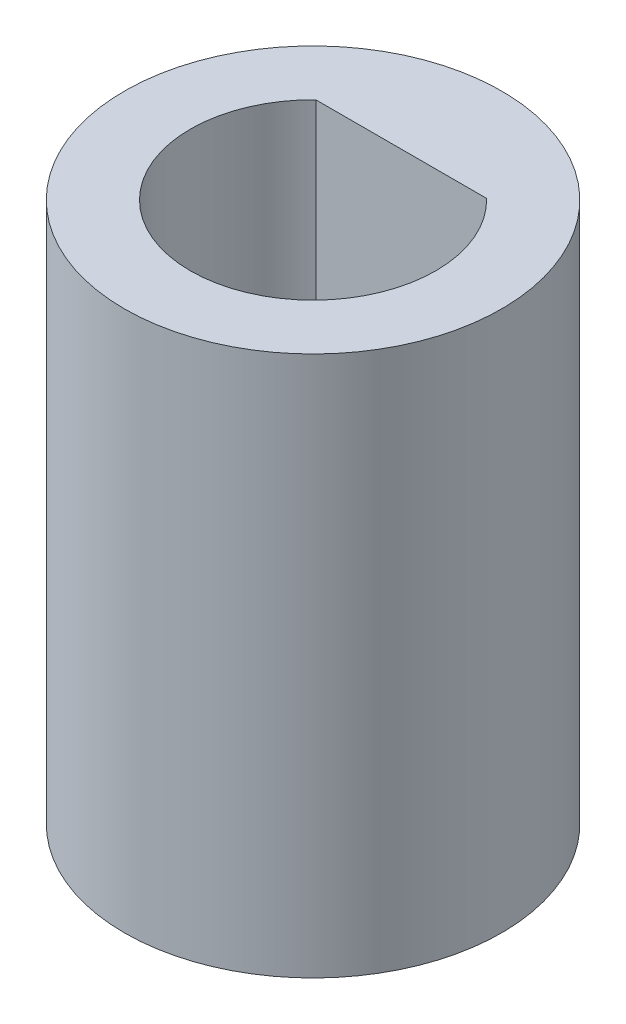
SolidWorks part; units mm, degrees
ref_plane "Front Plane" through (0, 0, 0) normal (0, 0, 1) x (1, 0, 0)
ref_plane "Top Plane" through (0, 0, 0) normal (0, 1, 0) x (1, 0, 0)
ref_plane "Right Plane" through (0, 0, 0) normal (1, 0, 0) x (0, 0, -1)
sketch "Sketch1" plane through (0, 0, 0) normal (0, 1, 0) x (1, 0, 0)
  line L0 (-2.5923, 2.675) -> (2.5923, 2.675) construction
  circle A0 centre (0, 0) radius 5.725
  circle A1 centre (0, 0) radius 3.725 construction
  arc A2 (-2.5923, 2.675) -> (2.5923, 2.675) centre (0, 0) ccw construction
  point P6 (0, -3.725)
  dimension "D1" = 7.45
  dimension "D2" = 2
  dimension "D3" = 6.4
extrude "Boss-Extrude1" add sketch "Sketch1" against normal blind 16.4
ref_plane "Plane1" through (0, 0, 0) normal (0, 1, 0) x (1, 0, 0)
sketch "Sketch3" plane through (0, 0, 0) normal (0, 1, 0) x (1, 0, 0)
  line L0 (-2.5923, 2.675) -> (2.5923, 2.675) construction
  line L1 (-2.5923, 2.675) -> (2.5923, 2.675)
  circle A0 centre (0, 0) radius 3.725 construction
  arc A1 (-2.5923, 2.675) -> (2.5923, 2.675) centre (0, 0) ccw
extrude "Cut-Extrude1" cut sketch "Sketch3" against normal through all
